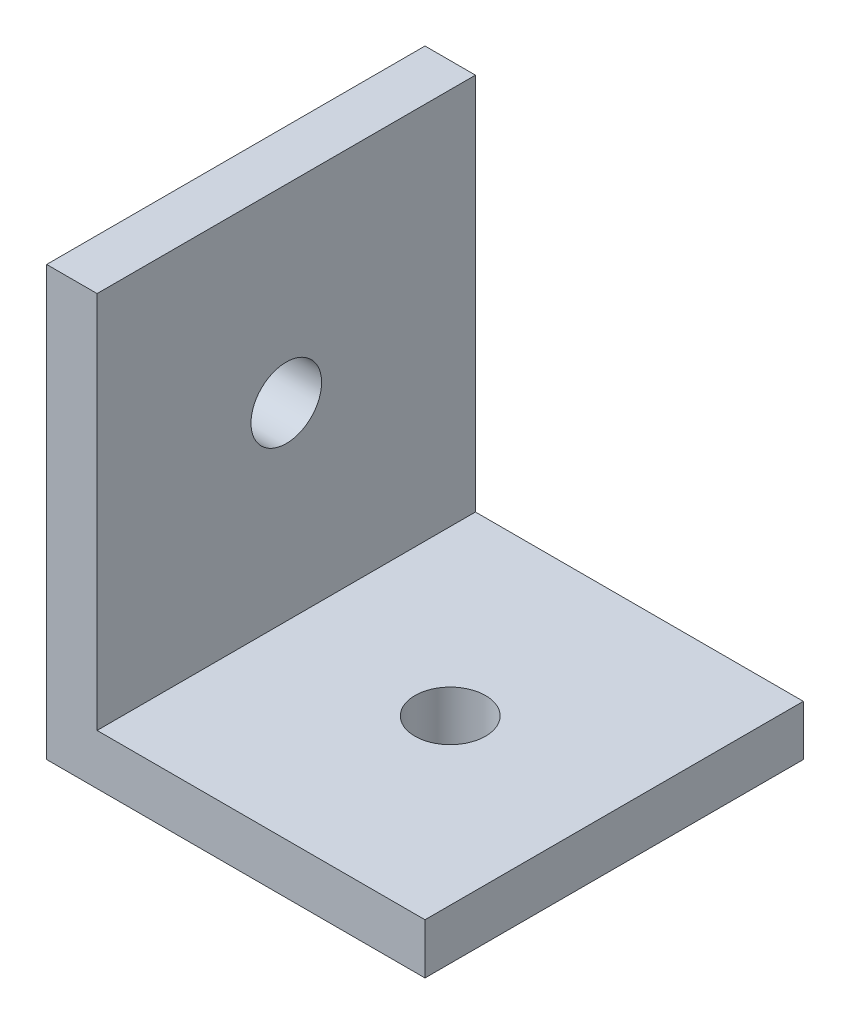
SolidWorks part; units mm, degrees
ref_plane "Front Plane" through (0, 0, 0) normal (0, 0, 1) x (1, 0, 0)
ref_plane "Top Plane" through (0, 0, 0) normal (0, 1, 0) x (1, 0, 0)
ref_plane "Right Plane" through (0, 0, 0) normal (1, 0, 0) x (0, 0, -1)
sketch "Sketch2" plane through (0, 0, 0) normal (0, 1, 0) x (1, 0, 0)
  line L1 (-6.0211, 4.1197) -> (8.9789, 4.1197)
  line L2 (-6.0211, 4.1197) -> (-6.0211, -10.8803)
  line L3 (-6.0211, -10.8803) -> (8.9789, -10.8803)
  line L4 (8.9789, 4.1197) -> (8.9789, -10.8803)
  dimension "D1" = 15
  dimension "D2" = 15
extrude "Boss-Extrude1" add sketch "Sketch2" along normal blind 2
sketch "Sketch3" plane through (0, 2, 0) normal (0, 1, 0) x (1, 0, 0)
  line L0 (-6.0211, -10.8803) -> (8.9789, -10.8803) construction
  line L1 (-6.0211, 4.1197) -> (-4.0211, 4.1197)
  line L2 (-6.0211, 4.1197) -> (-6.0211, -10.8803)
  line L3 (-6.0211, -10.8803) -> (-4.0211, -10.8803)
  line L4 (-4.0211, 4.1197) -> (-4.0211, -10.8803)
  dimension "D1" = 2
extrude "Boss-Extrude2" add sketch "Sketch3" along normal blind 15
sketch "Sketch4" plane through (0, 2, 0) normal (0, 1, 0) x (1, 0, 0)
  line L0 (-6.0211, -3.3803) -> (8.9789, -3.3803) construction
  line L1 (-6.0211, 4.1197) -> (-6.0211, -10.8803) construction
  line L2 (8.9789, -10.8803) -> (8.9789, 4.1197) construction
  line L3 (2.4789, 4.1197) -> (2.4789, -10.8803) construction
  line L4 (8.9789, 4.1197) -> (-4.0211, 4.1197) construction
  line L5 (-4.0211, -10.8803) -> (8.9789, -10.8803) construction
  circle A0 centre (2.4789, -3.3803) radius 1.4
  dimension "D1" = 2.8
extrude "Cut-Extrude1" cut sketch "Sketch4" against normal blind 15
sketch "Sketch5" plane through (-4.0211, 0, 0) normal (1, 0, 0) x (0, 0, -1)
  line L0 (-10.8803, 9.5) -> (4.1197, 9.5) construction
  line L1 (-10.8803, 17) -> (-10.8803, 2) construction
  line L2 (4.1197, 17) -> (4.1197, 2) construction
  line L3 (-10.8803, 0) -> (4.1197, 0) construction
  line L4 (-3.3803, 17) -> (-3.3803, 0) construction
  line L5 (-10.8803, 17) -> (4.1197, 17) construction
  circle A0 centre (-3.3803, 9.5) radius 1.4
  dimension "D2" = 2.8
  dimension "D1" = 9.5
extrude "Cut-Extrude2" cut sketch "Sketch5" against normal blind 15
